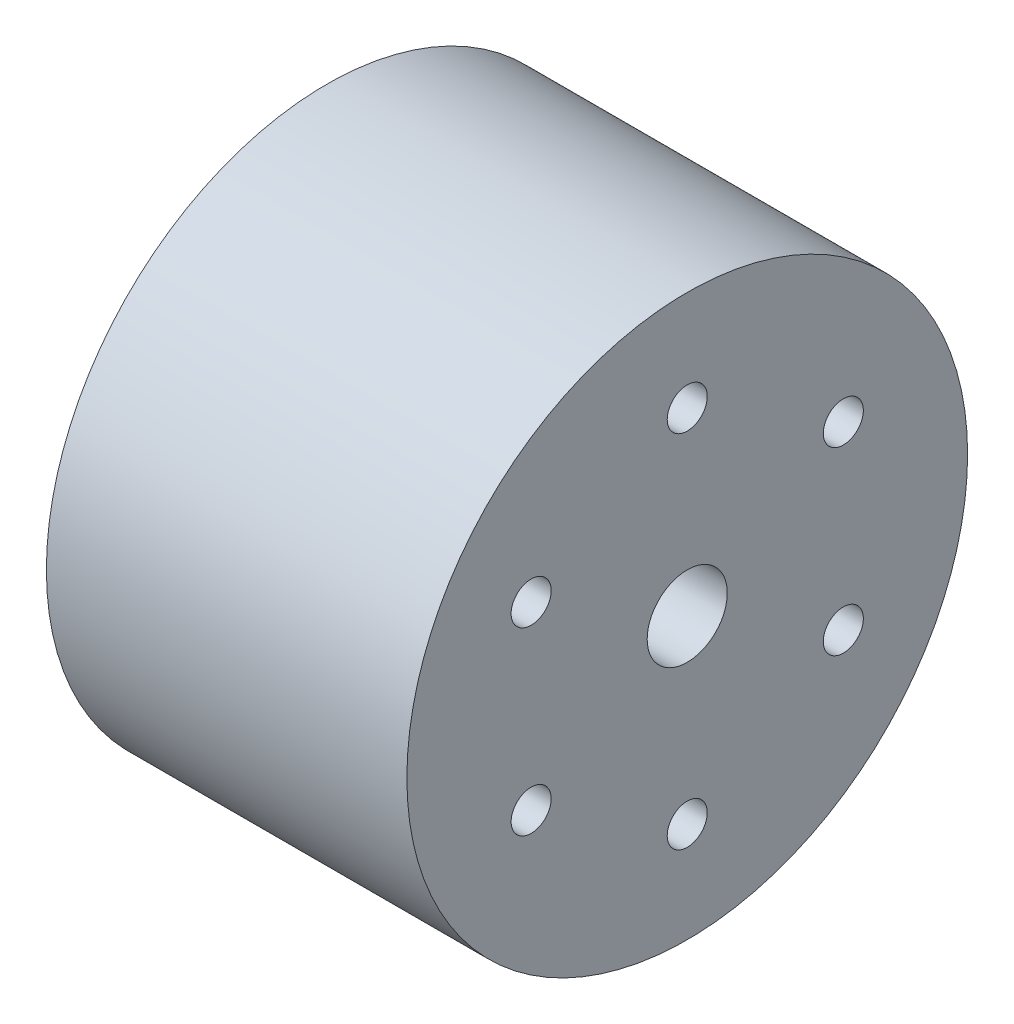
SolidWorks part; units mm, degrees
ref_plane "Front Plane" through (0, 0, 0) normal (0, 0, 1) x (1, 0, 0)
ref_plane "Top Plane" through (0, 0, 0) normal (0, 1, 0) x (1, 0, 0)
ref_plane "Right Plane" through (0, 0, 0) normal (1, 0, 0) x (0, 0, -1)
sketch "Sketch1" plane through (0, 0, 0) normal (0, 0, 1) x (1, 0, 0)
  line L0 (14.45, 35) -> (14.45, 16)
  line L1 (14.45, 16) -> (19.45, 16)
  line L2 (19.45, 16) -> (19.45, 5)
  line L3 (19.45, 5) -> (59.45, 5)
  line L4 (59.45, 5) -> (59.45, 35)
  line L5 (59.45, 35) -> (14.45, 35)
  line L6 (14.45, -33) -> (14.45, 33) construction
  line L7 (19.45, 16) -> (14.45, 16) construction
  line L8 (19.45, -16) -> (19.45, 16) construction
  line L9 (0, 0) -> (59.45, 0) construction
  dimension "D1" = 45
  dimension "D2" = 30
revolve "Revolve1" add sketch "Sketch1" angle 360 about L9
sketch "Sketch2" plane through (14.45, 0, 0) normal (-1, 0, 0) x (0, 0, 1)
  circle A0 centre (19.4856, 11.25) radius 2.5
  circle A2 centre (19.4856, -11.25) radius 2.5
  circle A3 centre (0, -22.5) radius 2.5
  circle A4 centre (-19.4856, -11.25) radius 2.5
  circle A5 centre (-19.4856, 11.25) radius 2.5
  circle A6 centre (0, 22.5) radius 2.5
  circle A9 centre (19.4856, 11.25) radius 2.5 construction
  point P20 (0, 0)
  dimension "D1" = 6
extrude "Cut-Extrude1" cut sketch "Sketch2" against normal up to surface (45 mm away) up to face at (59.45, 0, 35)
